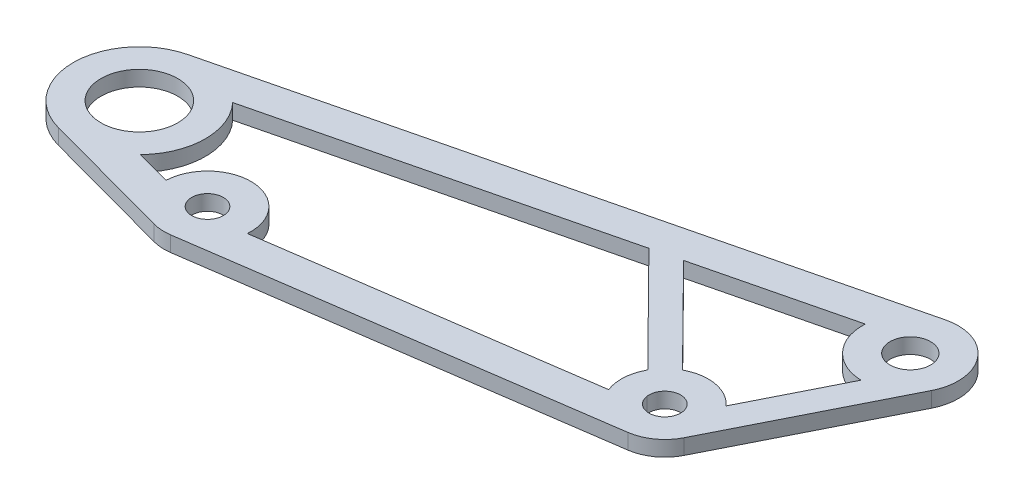
SolidWorks part; units mm, degrees
material "6061-T6 (SS)"
ref_plane "Front Plane" through (0, 0, 0) normal (0, 0, 1) x (1, 0, 0)
ref_plane "Top Plane" through (0, 0, 0) normal (0, 1, 0) x (1, 0, 0)
ref_plane "Right Plane" through (0, 0, 0) normal (1, 0, 0) x (0, 0, -1)
sketch "Sketch1" plane through (0, 0, 0) normal (0, 1, 0) x (1, 0, 0)
  line L0 (0, 0) -> (124.8778, 34.4406) construction
  line L1 (124.8778, 34.4406) -> (108.585, 0) construction
  line L2 (108.585, 0) -> (0, 0) construction
  line L3 (-3.2476, 13.2606) -> (122.5214, 44.0623)
  line L5 (116.6057, -4.036) -> (133.7266, 29.9879)
  line L6 (108.585, 0) -> (109.8191, -8.8937) construction
  line L7 (-1.8881, 7.7097) -> (123.8808, 38.5113)
  line L8 (111.5006, -1.4671) -> (128.6215, 32.5568)
  line L9 (0.3416, -7.9301) -> (108.7255, -3.2609)
  line L10 (108.585, 0) -> (80.9067, 27.9867) construction
  line L11 (108.585, 0) -> (108.585, 29.9472) construction
  line L12 (74.1927, 26.3424) -> (50.6623, -5.7623) construction
  line L13 (78.0308, 27.2823) -> (53.9142, -5.6222)
  line L14 (70.3546, 25.4024) -> (47.4105, -5.9024)
  line L15 (78.0308, 27.2823) -> (100.7231, 4.3373)
  line L16 (83.7825, 28.691) -> (104.3351, 7.9094)
  line L17 (62.4275, 10.29) -> (60.3789, 11.7916) construction
  line L18 (62.4275, 10.29) -> (64.4762, 8.7885) construction
  line L19 (94.7458, 13.9933) -> (92.9399, 12.2073) construction
  line L20 (94.7458, 13.9933) -> (96.5518, 15.7794) construction
  line L21 (114.3014, 6.9241) -> (123.2323, 24.6722)
  line L22 (0.5876, -13.6398) -> (108.9715, -8.9706)
  line L23 (9.9856, 9.3101) -> (114.9891, 35.0261)
  line L24 (12.1896, -6.1485) -> (99.9242, -2.3689)
  line L25 (0, 0) -> (25.9814, -11.8952) construction
  line L26 (-3.5765, -13.1757) -> (23.6293, -20.5606)
  line L27 (27.2612, -20.7824) -> (109.8648, -8.8872)
  line L28 (26.4466, -15.1258) -> (109.0502, -3.2306)
  line L29 (25.1264, -15.0451) -> (-2.0793, -7.6603)
  line L30 (2.4097, -7.5629) -> (22.9653, -13.1426)
  line L31 (28.8233, -13.5004) -> (106.3115, -2.3419)
  circle A0 centre (0, 0) radius 7.9375
  circle A1 centre (124.8778, 34.4406) radius 4.191
  circle A2 centre (108.585, 0) radius 3.2639
  circle A3 centre (0, 0) radius 13.6525
  circle A4 centre (108.585, 0) radius 8.9789
  circle A5 centre (124.8778, 34.4406) radius 9.906
  arc A6 (-3.2476, 13.2606) -> (4.8798, -12.7506) centre (0, 0) ccw
  arc A7 (116.6057, -4.036) -> (108.585, -8.9789) centre (108.585, 0) cw
  arc A8 (122.5214, 44.0623) -> (133.7266, 29.9879) centre (124.8778, 34.4406) cw
  circle A9 centre (25.9814, -11.8952) radius 3.2639
  circle A10 centre (25.9814, -11.8952) radius 8.9789
  dimension "D4" = 15.875
  dimension "D5" = 6.5278
  dimension "D6" = 8.382
  dimension "D7" = 5.715
  dimension "D8" = 5.715
  dimension "D9" = 5.715
  dimension "D19" = 6.5278
  dimension "D20" = 5.715
  dimension "D1" = 129.54
  dimension "D2" = 38.1
  dimension "D3" = 108.585
  dimension "D10" = 97.9
  dimension "D11" = 70
  dimension "D12" = 40
  dimension "D13" = 5.08
  dimension "D14" = 1.27
  dimension "D15" = 1.27
  dimension "D16" = 1.27
  dimension "D17" = 24.6
  dimension "D18" = 28.575
  dimension "D21" = 1.27
  dimension "D22" = 1.27
extrude "Boss-Extrude4" add sketch "Sketch1" against normal blind 3.175 contours A5 L7 A1 L8 | A5 L3 A3 L7 | A3 L9 A0 L7 | L9 A3 L7 A0 | A3 L23 L14 L7 | A4 L16 L23 L15 | L14 L23 L13 L7 | L15 L23 L16 L7 | A5 L7 L16 L23 | L13 L23 L15 | A5 L8 A4 L5 | L7 A5 L8 A1 | A4 L8 A2 L9 | L8 A4 L9 A2 | L29 A3 L30 L9 A0 | L30 A3 L9 | A0 L9 L30 | L9 A4 L28 A2 | L31 A4 L9 A2 | A10 L30 A3 L29 | A10 L22 A3 L26 | A10 L29 A3 L22 | L30 A10 L29 L22 | A9 L30 L22 L29 | A10 L28 A9 L29 L22 | L22 A10 L9 L30 A9 | L9 A10 L24 | L24 A10 | A9 L22 L30 | L28 A10 L31 A9 | L31 A10 L22 A9 | A4 L28 L22 | A10 L27 A4 L22 L28 | A10 L28 L22 L31 | A4 L9 L31 L22 L28 | A4 L31 L9 | L29 A10 L22
ref_plane "Plane1" through (108.585, 0, 0) normal (0.1374, 0, 0.9905) x (0.9905, 0, -0.1374)
split line "Split Line1"
sketch "Sketch2" [suppressed] plane through (0, -3.175, 0) normal (0, -1, 0) x (1, 0, 0)
  line L1 (69.4473, -23.6659) -> (60.7288, -1.2641)
  line L2 (62.8949, 2.1892) -> (101.6127, 5.2609)
  line L3 (101.2476, -37.8411) -> (79.7056, -31.0891)
  line L4 (79.2148, -26.4545) -> (98.3531, -15.6299)
  line L5 (59.9072, -25.992) -> (7.538, -8.592)
  line L6 (63.0965, -22.7173) -> (54.4829, 1.0899)
  line L7 (51.7805, 2.7463) -> (11.1946, -2.3078)
  line L8 (73.1912, -24.8791) -> (102.155, -6.1958)
  line L9 (104.5239, -35.0732) -> (102.1201, -17.4966)
  circle A0 centre (111.76, 0) radius 11.43 construction
  circle A3 centre (0, 0) radius 11.43 construction
  arc A4 (11.1946, -2.3078) -> (7.538, -8.592) centre (0, 0) cw
  arc A5 (101.6127, 5.2609) -> (102.155, -6.1958) centre (111.76, 0) ccw
  arc A6 (101.2476, -37.8411) -> (104.5239, -35.0732) centre (102.0073, -35.4173) ccw
  arc A7 (98.3531, -15.6299) -> (102.1201, -17.4966) centre (99.6035, -17.8407) cw
  arc A8 (69.4473, -23.6659) -> (73.1912, -24.8791) centre (71.8144, -22.7446) ccw
  arc A9 (60.7288, -1.2641) -> (62.8949, 2.1892) centre (63.0958, -0.3428) cw
  arc A10 (63.0965, -22.7173) -> (59.9072, -25.992) centre (60.7081, -23.5815) cw
  arc A11 (54.4829, 1.0899) -> (51.7805, 2.7463) centre (52.0944, 0.2257) ccw
  arc A12 (79.2148, -26.4545) -> (79.7056, -31.0891) centre (80.4653, -28.6654) ccw
  dimension "D1" = 2.54
  dimension "D2" = 2.54
  dimension "D3" = 2.54
  dimension "D4" = 2.54
  dimension "D5" = 2.54
  dimension "D6" = 2.54
  dimension "D7" = 2.54
extrude "Cut-Extrude2" [suppressed] cut sketch "Sketch2" against normal through all
fillet "Fillet1" [suppressed] radius 7.62
fillet "Fillet2" [suppressed] radius 3.81
fillet "Fillet3" [suppressed] radius 2.54
equation "\"x\"= .05"
